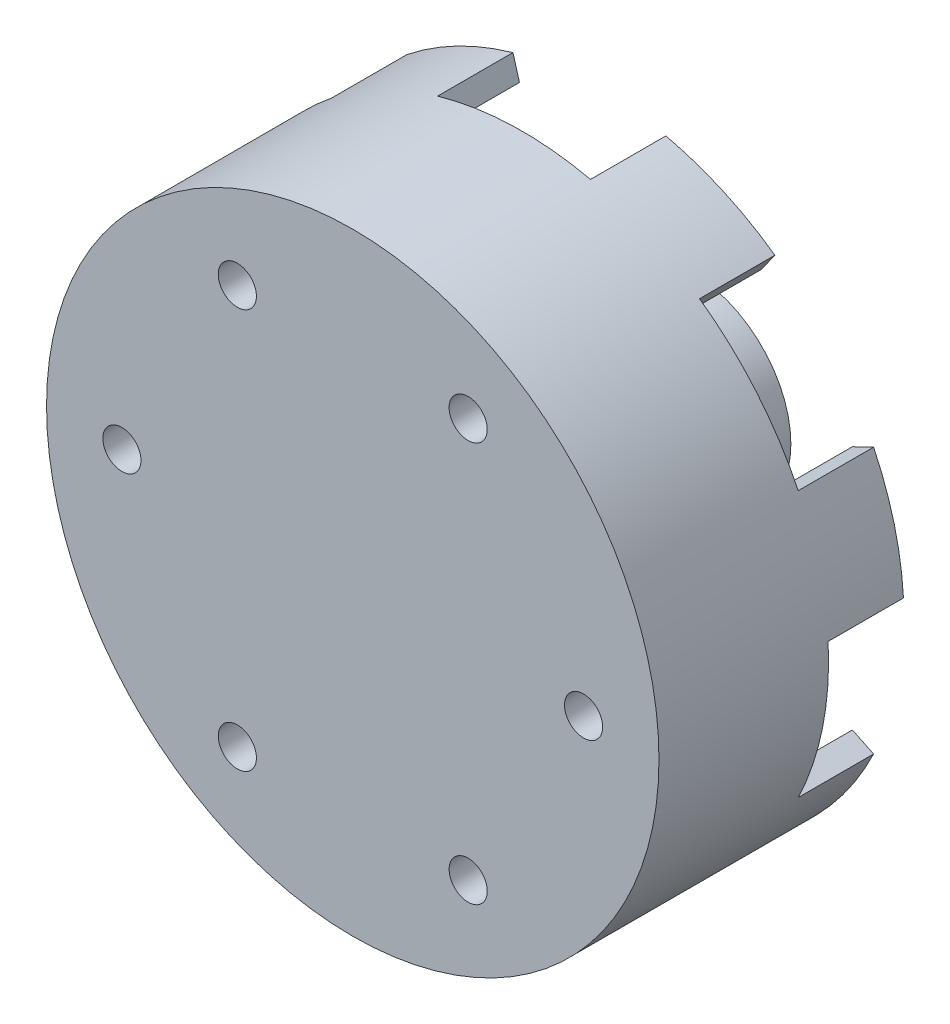
SolidWorks part; units mm, degrees
ref_plane "Front Plane" through (0, 0, 0) normal (0, 0, 1) x (1, 0, 0)
ref_plane "Top Plane" through (0, 0, 0) normal (0, 1, 0) x (1, 0, 0)
ref_plane "Right Plane" through (0, 0, 0) normal (1, 0, 0) x (0, 0, -1)
sketch "Sketch1" plane through (0, 0, 0) normal (0, 0, 1) x (1, 0, 0)
  circle A0 centre (0, 0) radius 10.5
  dimension "D1" = 21
extrude "Boss-Extrude1" add sketch "Sketch1" along normal blind 12
sketch "Sketch2" plane through (0, 0, 12) normal (0, 0, 1) x (1, 0, 0)
  circle A0 centre (0, 0) radius 12
  dimension "D1" = 24
extrude "Boss-Extrude2" add sketch "Sketch2" along normal blind 6
sketch "Sketch3" plane through (0, 0, 18) normal (0, 0, 1) x (1, 0, 0)
  circle A0 centre (0, 0) radius 32.5
  dimension "D1" = 65
extrude "Boss-Extrude3" add sketch "Sketch3" along normal blind 18
sketch "Sketch4" plane through (0, 0, 36) normal (0, 0, 1) x (1, 0, 0)
  circle A0 centre (0, 0) radius 24.5 construction
  circle A1 centre (24.5, 0) radius 2.025
  circle A2 centre (12.25, -21.2176) radius 2.025
  circle A3 centre (-12.25, -21.2176) radius 2.025
  circle A4 centre (-24.5, 0) radius 2.025
  circle A5 centre (-12.25, 21.2176) radius 2.025
  circle A6 centre (12.25, 21.2176) radius 2.025
  point P17 (0, 0)
  dimension "D1" = 49
  dimension "D2" = 4.05
  dimension "D3" = 6
extrude "Cut-Extrude1" cut sketch "Sketch4" against normal through all
sketch "Sketch5" plane through (0, 0, 18) normal (0, 0, -1) x (-1, 0, 0)
  line L0 (0, 0) -> (33.2011, 0) construction
  line L1 (0, 0) -> (30.0261, 12.4372) construction
  line L2 (27.7164, 11.4805) -> (30.0261, 12.4372)
  line L3 (30, 0) -> (32.5, 0)
  line L4 (26.2567, -14.5116) -> (28.4448, -15.7209)
  line L5 (18.7047, -23.4549) -> (20.2634, -25.4095)
  line L6 (5.0252, -29.5761) -> (5.444, -32.0408)
  line L7 (-6.6756, -29.2478) -> (-7.2319, -31.6852)
  line L8 (-19.9904, -22.3693) -> (-21.6563, -24.2334)
  line L9 (-27.0291, -13.0165) -> (-29.2815, -14.1012)
  line L10 (-29.9528, 1.6821) -> (-32.4489, 1.8223)
  line L11 (-27.0291, 13.0165) -> (-29.2815, 14.1012)
  line L12 (-17.3601, 24.4668) -> (-18.8068, 26.5057)
  line L13 (-6.6756, 29.2478) -> (-7.2319, 31.6852)
  line L14 (8.3051, 28.8275) -> (8.9972, 31.2298)
  line L15 (18.7047, 23.4549) -> (20.2634, 25.4095)
  arc A0 (32.5, 0) -> (30.0261, 12.4372) centre (0, 0) ccw
  arc A1 (30, 0) -> (27.7164, 11.4805) centre (0, 0) ccw
  arc A2 (20.2634, -25.4095) -> (28.4448, -15.7209) centre (0, 0) ccw
  arc A3 (18.7047, -23.4549) -> (26.2567, -14.5116) centre (0, 0) ccw
  arc A4 (-7.2319, -31.6852) -> (5.444, -32.0408) centre (0, 0) ccw
  arc A5 (-6.6756, -29.2478) -> (5.0252, -29.5761) centre (0, 0) ccw
  arc A6 (-29.2815, -14.1012) -> (-21.6563, -24.2334) centre (0, 0) ccw
  arc A7 (-27.0291, -13.0165) -> (-19.9904, -22.3693) centre (0, 0) ccw
  arc A8 (-29.2815, 14.1012) -> (-32.4489, 1.8223) centre (0, 0) ccw
  arc A9 (-27.0291, 13.0165) -> (-29.9528, 1.6821) centre (0, 0) ccw
  arc A10 (-7.2319, 31.6852) -> (-18.8068, 26.5057) centre (0, 0) ccw
  arc A11 (-6.6756, 29.2478) -> (-17.3601, 24.4668) centre (0, 0) ccw
  arc A12 (20.2634, 25.4095) -> (8.9972, 31.2298) centre (0, 0) ccw
  arc A13 (18.7047, 23.4549) -> (8.3051, 28.8275) centre (0, 0) ccw
  point P4 (27.7164, 11.4805)
  point P34 (0, 0)
  dimension "D1" = 2.5
  dimension "D2" = 7
extrude "Boss-Extrude4" add sketch "Sketch5" along normal blind 8
